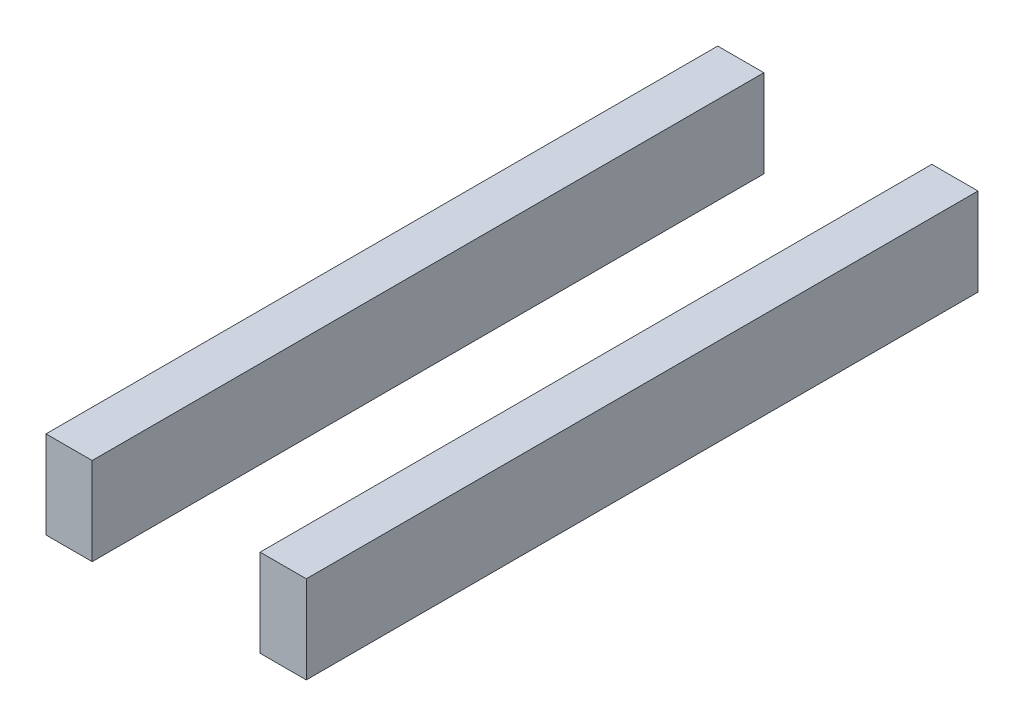
SolidWorks part; units mm, degrees
ref_plane "Спереди" through (0, 0, 0) normal (0, 0, 1) x (1, 0, 0)
ref_plane "Сверху" through (0, 0, 0) normal (0, 1, 0) x (1, 0, 0)
ref_plane "Справа" through (0, 0, 0) normal (1, 0, 0) x (0, 0, -1)
sketch "Эскиз1" plane through (0, 0, 0) normal (0, 1, 0) x (1, 0, 0)
  line L0 (7.6698, 0.3168) -> (4.5082, 0.3168)
  line L1 (-6.6756, 0) -> (-9.8372, 0)
  line L2 (-6.6756, 0) -> (-6.6756, -45.9976)
  line L3 (-6.6756, -45.9976) -> (-9.8372, -45.9976)
  line L4 (-9.8372, 0) -> (-9.8372, -45.9976)
  line L5 (7.6698, 0.3168) -> (7.6698, -45.6809)
  line L6 (7.6698, -45.6809) -> (4.5082, -45.6809)
  line L7 (4.5082, 0.3168) -> (4.5082, -45.6809)
extrude "Бобышка-Вытянуть2" add sketch "Эскиз1" along normal blind 6
